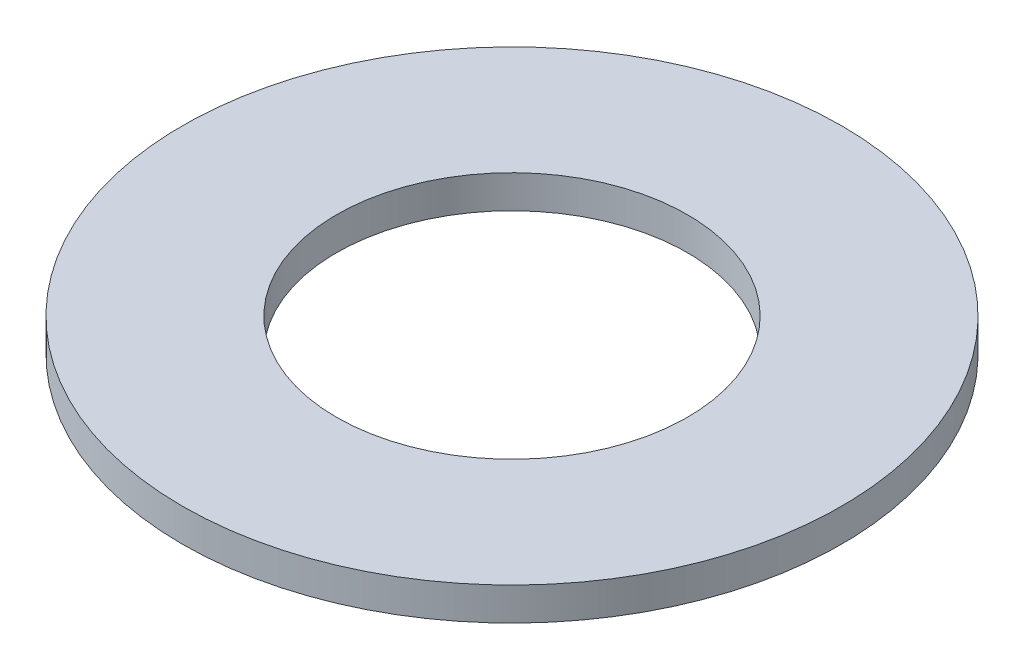
SolidWorks part; units mm, degrees
ref_plane "Front Plane" through (0, 0, 0) normal (0, 0, 1) x (1, 0, 0)
ref_plane "Top Plane" through (0, 0, 0) normal (0, 1, 0) x (1, 0, 0)
ref_plane "Right Plane" through (0, 0, 0) normal (1, 0, 0) x (0, 0, -1)
sketch "Sketch1" plane through (0, 0, 0) normal (0, 1, 0) x (1, 0, 0)
  circle A0 centre (0, 0) radius 50.8
  circle A1 centre (0, 0) radius 27.051
  dimension "D1" = 101.6
  dimension "D2" = 54.102
extrude "Boss-Extrude1" add sketch "Sketch1" along normal blind 5.08
